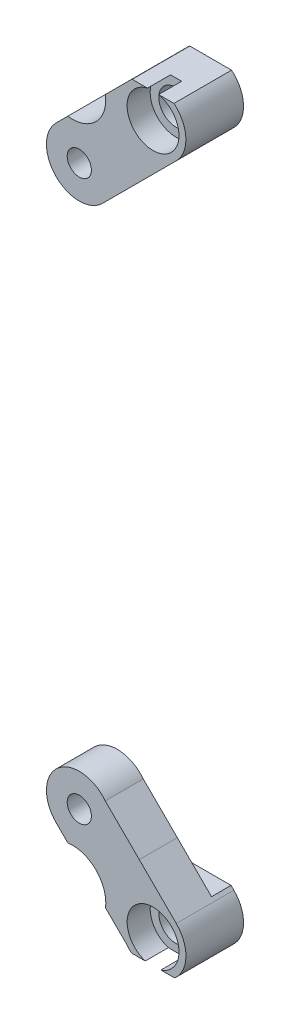
SolidWorks part; units mm, degrees
ref_plane "Спереди" through (0, 0, 0) normal (0, 0, 1) x (1, 0, 0)
ref_plane "Сверху" through (0, 0, 0) normal (0, 1, 0) x (1, 0, 0)
ref_plane "Справа" through (0, 0, 0) normal (1, 0, 0) x (0, 0, -1)
sketch "Skizze8" plane through (0, 0, 0) normal (0, 0, 1) x (1, 0, 0)
  line L4 (-51.9925, 25.9023) -> (-50.9797, 26.9151)
  line L5 (-44.7807, 25.0531) -> (-41.5618, 28.2709)
  line L6 (-45.3915, 32.484) -> (-41.762, 32.484)
  line L7 (-47.7053, 30.1895) -> (-45.5925, 32.3023)
  line L12 (-51.9754, -26.6784) -> (-50.9703, -27.6768)
  line L13 (-47.6985, -30.9265) -> (-45.8565, -32.756)
  line L14 (-41.6982, -33.1953) -> (-45.4496, -33.1953)
  line L15 (-41.5624, -29.0306) -> (-44.7702, -25.8346)
  line L16 (-44.7807, 25.0531) -> (-48.0061, 21.8288)
  line L17 (-45.5925, 32.3023) -> (-45.3915, 32.484)
  line L18 (-44.7702, -25.8346) -> (-47.7218, -22.903)
  arc A5 (-51.9925, 25.9023) -> (-52.8239, 23.8904) centre (-49.9739, 23.8904) ccw
  arc A6 (-41.5618, 28.2709) -> (-41.762, 32.484) centre (-43.5767, 30.2865) ccw
  arc A7 (-50.9797, 26.9151) -> (-47.7053, 30.1895) centre (-50.5773, 29.787) ccw
  circle A8 centre (-49.9739, 23.8904) radius 1.05
  circle A9 centre (-43.5767, 30.2865) radius 1.5
  circle A16 centre (-49.9739, -24.6496) radius 1.05
  arc A17 (-52.8239, -24.6496) -> (-51.9754, -26.6784) centre (-49.9739, -24.6496) ccw
  arc A18 (-45.8565, -32.756) -> (-45.4496, -33.1953) centre (-43.5739, -31.0496) ccw
  arc A19 (-47.6985, -30.9265) -> (-50.9703, -27.6768) centre (-50.5739, -30.5496) ccw
  circle A20 centre (-43.5739, -31.0496) radius 1.5
  arc A21 (-41.6982, -33.1953) -> (-41.5624, -29.0306) centre (-43.5739, -31.0496) ccw
  circle A22 centre (-49.9739, 23.8904) radius 2.85
  circle A23 centre (-49.9739, -24.6496) radius 2.85
extrude "Aufsatz-Linear austragen2" add sketch "Skizze8" along normal blind 5 contours A23 L12 A19 L13 A18 L14 A21 L15 L18 A20 | A23 A17 A16 | A22 L16 L5 A6 L6 L17 L7 A7 L4 A9 | A5 A22 L16 A8
sketch "Skizze10" plane through (0, 0, 0) normal (0, 0, -1) x (-1, 0, 0)
  line L1 (37.243, 28.0736) -> (57.3086, 28.0736)
  line L2 (37.243, 28.0736) -> (37.243, -28.7892)
  line L3 (37.243, -28.7892) -> (57.3086, -28.7892)
  line L4 (57.3086, 28.0736) -> (57.3086, -28.7892)
extrude "Schnitt-Linear austragen6" cut sketch "Skizze10" against normal blind 1.7
sketch "Skizze11" plane through (0, 0, 5) normal (0, 0, 1) x (1, 0, 0)
  circle A0 centre (-43.5767, 30.2865) radius 2.25
  circle A1 centre (-43.5739, -31.0496) radius 2.25
  dimension "D1" = 4.5
extrude "Schnitt-Linear austragen7" cut sketch "Skizze11" against normal blind 2
